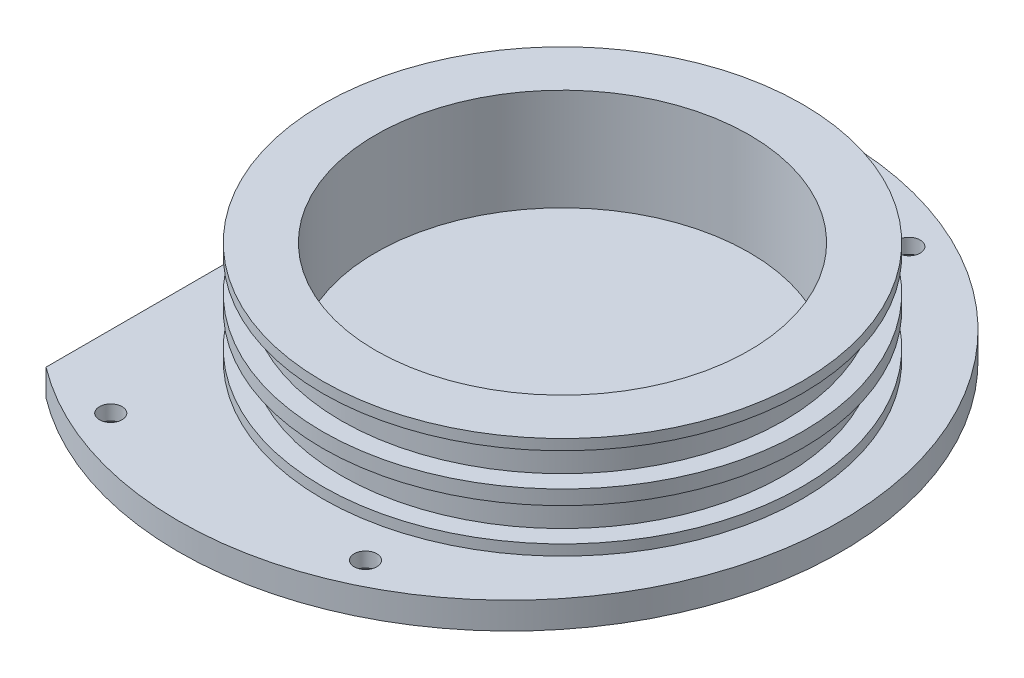
SolidWorks part; units mm, degrees
ref_plane "Front" through (0, 0, 0) normal (0, 0, 1) x (1, 0, 0)
ref_plane "Top" through (0, 0, 0) normal (0, 1, 0) x (1, 0, 0)
ref_plane "Right" through (0, 0, 0) normal (1, 0, 0) x (0, 0, -1)
sketch "Sketch1" plane through (0, 0, 0) normal (0, 1, 0) x (1, 0, 0)
  line L0 (-48.4463, 0) -> (41.648, 0) construction
  line L1 (-48.4463, -28.4211) -> (-48.4463, 28.4211)
  circle A0 centre (-7.882, 0) radius 49.53
  point P4 (-3.3991, 0)
  dimension "D1" = 99.06
  dimension "D3" = 7.882
  dimension "D2" = 56.8422
extrude "Boss-Extrude1" add sketch "Sketch1" along normal blind 4 contours L1 L0 A0 | L0 L1 A0
sketch "Sketch2" plane through (0, 4, 0) normal (0, 1, 0) x (1, 0, 0)
  circle A0 centre (0, 0) radius 35.8855
  circle A1 centre (0, 0) radius 27.94
  dimension "D1" = 71.771
  dimension "D2" = 55.88
extrude "Boss-Extrude2" add sketch "Sketch2" along normal blind 15.24
sketch "Sketch5" plane through (0, 0, 0) normal (1, 0, 0) x (0, 0, -1)
  line L0 (-35.8855, 19.24) -> (-35.8855, 4) construction
  line L1 (-35.8855, 5.5875) -> (-33.0788, 5.5875)
  line L2 (-35.8855, 5.5875) -> (-35.8855, 10.5405)
  line L3 (-35.8855, 10.5405) -> (-33.0788, 10.5405)
  line L4 (-33.0788, 5.5875) -> (-33.0788, 10.5405)
  line L5 (49.53, 4) -> (-49.53, 4) construction
  line L6 (-35.8855, 12.6995) -> (-33.0788, 12.6995)
  line L7 (-35.8855, 12.6995) -> (-35.8855, 17.6525)
  line L8 (-35.8855, 17.6525) -> (-33.0788, 17.6525)
  line L9 (-33.0788, 12.6995) -> (-33.0788, 17.6525)
  line L10 (35.8855, 19.24) -> (-35.8855, 19.24) construction
  dimension "D1" = 4.953
  dimension "D2" = 33.0788
  dimension "D3" = 1.5875
  dimension "D4" = 1.5875
ref_axis "Axis1" through (0, 19.24, 0) along (0, -1, 0)
revolve "Cut-Revolve1" cut sketch "Sketch5" angle 360 about axis through (0, 19.24, 0) along (0, -1, 0)
sketch "Sketch10" plane through (0, 0, 0) normal (0, -1, 0) x (1, 0, 0)
  line L0 (-48.4463, 28.4211) -> (-48.4463, -28.4211) construction
  line L1 (-48.4463, 39.5158) -> (-37.7438, 39.5158)
  line L2 (-48.4463, 39.5158) -> (-48.4463, -39.5158)
  line L3 (-48.4463, -39.5158) -> (-37.7438, -39.5158)
  line L4 (-37.7438, 39.5158) -> (-37.7438, -39.5158)
  arc A0 (-48.4463, -28.4211) -> (-48.4463, 28.4211) centre (-7.882, 0) ccw construction
  dimension "D1" = 10.7025
extrude "Cut-Extrude2" cut sketch "Sketch10" against normal through all
sketch "Sketch11" plane through (0, 0, 0) normal (0, -1, 0) x (-1, 0, 0)
  line L1 (26.932, 40.64) -> (-11.168, 40.64)
  line L2 (26.932, 40.64) -> (26.932, -40.64)
  line L3 (26.932, -40.64) -> (-11.168, -40.64)
  line L4 (-11.168, 40.64) -> (-11.168, -40.64)
  line L5 (26.932, 40.64) -> (-11.168, -40.64) construction
  line L6 (26.932, -40.64) -> (-11.168, 40.64) construction
  point P0 (7.882, 0)
  dimension "D1" = 81.28
  dimension "D2" = 38.1
hole_wizard "CSK for M3 Flat Head Machine Screw1" positions "Sketch12" profile "Sketch13" countersink size "M3" standard "ANSI Metric" end condition through all
sketch "Sketch12" plane through (0, 0, 0) normal (0, -1, 0) x (-1, 0, 0)
  point P0 (26.932, -40.64)
  point P3 (-11.168, -40.64)
  point P6 (-11.168, 40.64)
  point P9 (26.932, 40.64)
sketch "Sketch13" plane through (-26.932, 0, 40.64) normal (1, 0, 0) x (0, 0, -1)
  line L0 (0, 0) -> (0, 19.24)
  line L1 (0, 19.24) -> (1.7, 19.24)
  line L2 (1.7, 19.24) -> (1.7, 1.8)
  line L3 (1.7, 1.8) -> (3.5, 0)
  line L5 (3.5, 0) -> (0, 0)
  line L6 (-1.7, 1.8) -> (-3.5, 0) construction
  line L11 (0, -6.35) -> (0, 107.95) construction
  dimension "Thru Hole Dia." = 3.4
  dimension "Thru Hole Depth" = 19.24
  dimension "Near C'Sink Dia." = 7
  dimension "Near C'Sink Angle" = 90
equation "\"D1@Sketch2\"=2.865in-1mm"
equation "\"D2@Sketch5\"=(2.644in-1mm)/2"
equation "\"D1@Sketch10\"=0.40561024in+0.4mm"
